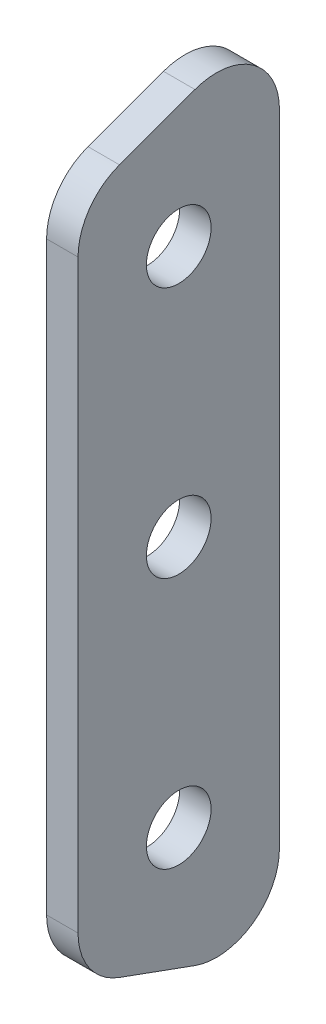
SolidWorks part; units mm, degrees
ref_plane "Front Plane" through (0, 0, 0) normal (0, 0, 1) x (1, 0, 0)
ref_plane "Top Plane" through (0, 0, 0) normal (0, 1, 0) x (1, 0, 0)
ref_plane "Right Plane" through (0, 0, 0) normal (1, 0, 0) x (0, 0, -1)
sketch "Sketch1" plane through (0, 0, 0) normal (1, 0, 0) x (0, 0, -1)
  line L0 (27.5, -45) -> (27.5, 45)
  line L1 (27.5, 45) -> (-27.5, 25)
  line L2 (-27.5, 25) -> (-27.5, -25)
  line L3 (-27.5, -25) -> (27.5, -45)
  line L4 (-27.5, 0) -> (27.5, 0) construction
  dimension "D1" = 90
  dimension "D2" = 50
  dimension "D3" = 55
sketch "Sketch2" plane through (0, 0, 0) normal (1, 0, 0) x (0, 0, -1)
  line L9 (4.64, 33.9846) -> (4.64, -33.9846)
  line L10 (4.64, 33.9846) -> (-26.632, 22.6129) construction
  line L11 (4.64, -33.9846) -> (24.96, -41.3736)
  line L12 (-26.632, -22.6129) -> (24.96, -41.3736)
  line L13 (24.96, 41.3736) -> (-26.632, 22.6129)
  line L14 (24.96, -41.3736) -> (24.96, 41.3736)
  line L15 (-26.632, -22.6129) -> (4.64, -33.9846) construction
  line L16 (24.96, 41.3736) -> (4.64, 33.9846)
  line L17 (24.96, -41.3736) -> (24.96, 41.3736)
  point P2 (3.5535, -39.861)
  point P3 (4.0915, -33.9846)
  point P5 (4.1721, 33.9846)
  dimension "D2" = 20.32
  dimension "D1" = 2.54
extrude "Boss-Extrude1" add sketch "Sketch2" along normal mid plane 3.175
sketch "Sketch5" plane through (1.5875, 0, 0) normal (1, 0, 0) x (0, 0, -1)
  line L0 (4.64, 0) -> (24.96, 0) construction
  line L1 (4.64, 33.9846) -> (4.64, -33.9846) construction
  line L2 (24.96, -41.3736) -> (24.96, 41.3736) construction
  line L4 (14.8, 0) -> (14.8, 25.4) construction
  line L5 (14.8, 0) -> (14.8, -25.4) construction
  point P0 (14.8, 0)
  point P2 (14.8, 25.4)
  point P4 (14.8, -25.4)
  dimension "D1" = 25.4
  dimension "D2" = 25.4
hole_wizard "1/4 Clearance Hole1" positions "Sketch5" profile "Sketch4" hole size "1/4" standard "ANSI Inch" end condition through all
sketch "Sketch4" plane through (1.5875, 0, -14.8) normal (0, 1, 0) x (0, 0, -1)
  line L0 (0, 0) -> (0, 3.175)
  line L1 (0, 3.175) -> (3.2639, 3.175)
  line L2 (3.2639, 3.175) -> (3.2639, 0)
  line L5 (3.2639, 0) -> (0, 0)
  line L11 (0, -6.35) -> (0, 107.95) construction
  dimension "Thru Hole Dia." = 6.5278
  dimension "Thru Hole Depth" = 3.175
fillet "Fillet1" radius 6.35 4 edges at (0, -33.9846, -4.64) (0, -41.3736, -24.96) (0, 41.3736, -24.96) (0, 33.9846, -4.64)
equation "\"D1@Sketch1\"=90mm"
equation "\"D2@Sketch1\"=50mm"
equation "\"D3@Sketch1\"=55mm"
